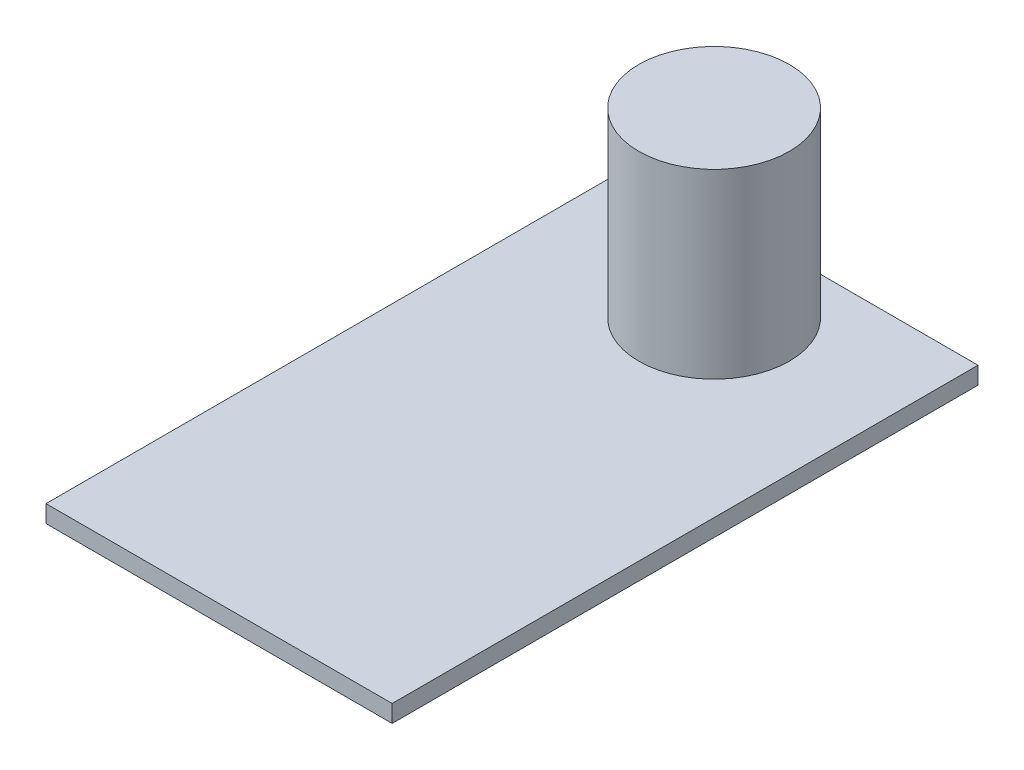
SolidWorks part; units mm, degrees
ref_plane "Front Plane" through (0, 0, 0) normal (0, 0, 1) x (1, 0, 0)
ref_plane "Top Plane" through (0, 0, 0) normal (0, 1, 0) x (1, 0, 0)
ref_plane "Right Plane" through (0, 0, 0) normal (1, 0, 0) x (0, 0, -1)
sketch "Sketch1" plane through (0, 0, 0) normal (0, 1, 0) x (1, 0, 0)
  line L1 (-40, 67.7) -> (0, 67.7)
  line L2 (-40, 67.7) -> (-40, 0)
  line L3 (-40, 0) -> (0, 0)
  line L4 (0, 67.7) -> (0, 0)
  dimension "D1" = 40
  dimension "D2" = 67.7
extrude "Boss-Extrude1" add sketch "Sketch1" along normal blind 2
sketch "Sketch2" plane through (0, 2, 0) normal (0, 1, 0) x (1, 0, 0)
  line L0 (0, 67.7) -> (-40, 67.7) construction
  line L1 (0, 0) -> (0, 67.7) construction
  circle A0 centre (-20, 57.2) radius 8.7
  point P6 (-104.46, 92.8215)
  dimension "D1" = 17.4
  dimension "D2" = 10.5
  dimension "D3" = 20
extrude "Boss-Extrude2" add sketch "Sketch2" along normal blind 21
